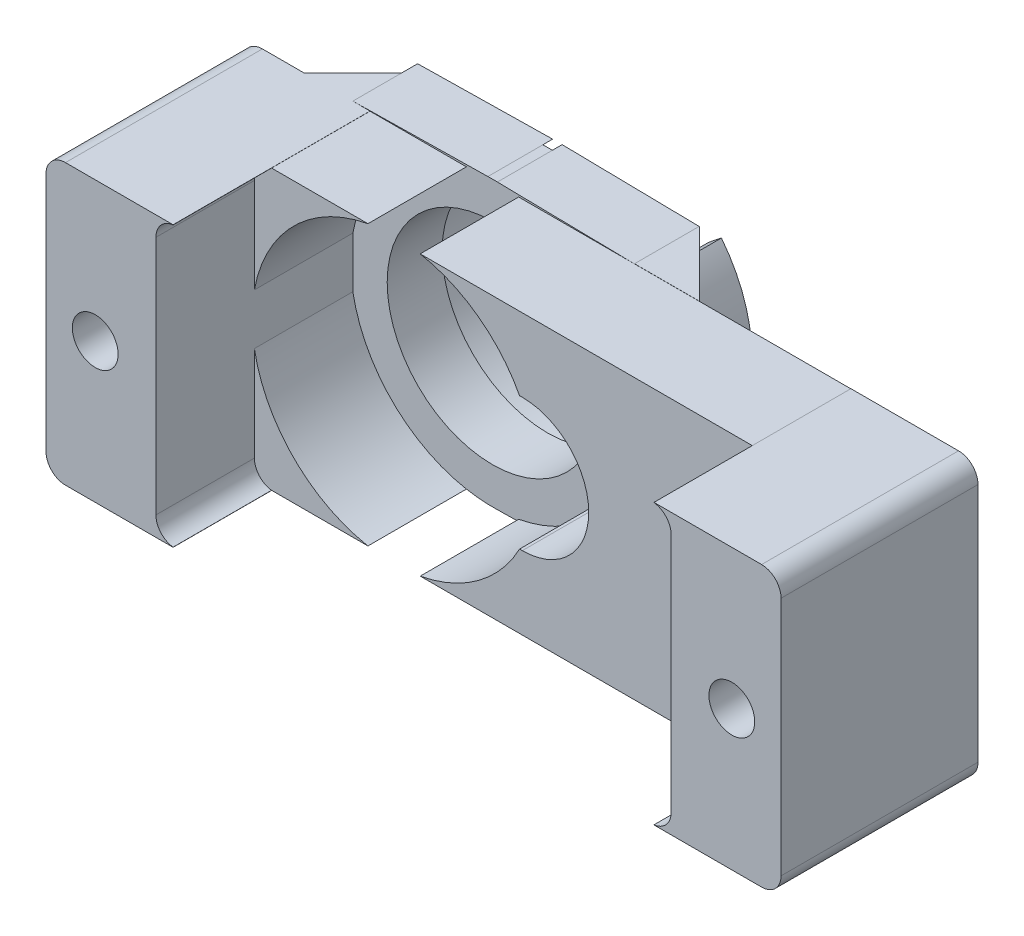
SolidWorks part; units mm, degrees
ref_plane "Front Plane" through (0, 0, 0) normal (0, 0, 1) x (1, 0, 0)
ref_plane "Top Plane" through (0, 0, 0) normal (0, 1, 0) x (1, 0, 0)
ref_plane "Right Plane" through (0, 0, 0) normal (1, 0, 0) x (0, 0, -1)
sketch "Sketch1" plane through (0, 0, 0) normal (0, 0, 1) x (1, 0, 0)
  line L1 (-16.05, -6.1) -> (16.05, -6.1)
  line L2 (-16.05, -6.1) -> (-16.05, 6.1)
  line L3 (-16.05, 6.1) -> (16.05, 6.1)
  line L4 (16.05, -6.1) -> (16.05, 6.1)
  line L5 (-16.05, -6.1) -> (16.05, 6.1) construction
  line L6 (-16.05, 6.1) -> (16.05, -6.1) construction
  point P0 (0, 0)
  dimension "D1" = 32.1
  dimension "D2" = 12.2
extrude "Boss-Extrude1" add sketch "Sketch1" along normal blind 4.3
fillet "Fillet1" radius 0.85 4 edges at (-16.05, -6.1, 2.15) (16.05, -6.1, 2.15) (16.05, 6.1, 2.15) (-16.05, 6.1, 2.15)
sketch "Sketch2" plane through (0, 0, 0) normal (0, 0, -1) x (-1, 0, 0)
  line L2 (-11.15, 5.25) -> (-11.15, -5.25)
  line L3 (-11.15, 5.25) -> (-11.15, -5.25) construction
  line L4 (-15.2, -6.1) -> (15.2, -6.1)
  line L5 (16.05, -5.25) -> (16.05, 5.25)
  line L6 (15.2, 6.1) -> (-15.2, 6.1)
  line L7 (-16.05, 5.25) -> (-16.05, -5.25)
  line L8 (-15.2, -6.1) -> (15.2, -6.1)
  line L9 (16.05, -5.25) -> (16.05, 5.25)
  line L10 (15.2, 6.1) -> (-15.2, 6.1)
  line L11 (-16.05, 5.25) -> (-16.05, -5.25)
  line L12 (-10.4, 6.1) -> (10.4, 6.1)
  line L13 (10.4, 6) -> (10.4, 6.1)
  line L14 (-10.4, 6) -> (-10.4, 6.1)
  line L15 (24.5614, 0) -> (-24.5614, 0) construction
  line L16 (0, -7.6317) -> (0, 7.6317) construction
  line L17 (11.15, 5.25) -> (11.15, -5.25)
  line L18 (-11.25, 5.25) -> (-11.25, -5.25)
  line L19 (-10.5, -6.0941) -> (-10.5, -6.2)
  line L20 (-10.5, -6.2) -> (10.5, -6.2)
  line L21 (10.5, -6.0941) -> (10.5, -6.2)
  line L22 (-10.4, -6) -> (-10.4, -6.1)
  line L23 (10.4, -6) -> (10.4, -6.1)
  line L24 (-10.4, -6.1) -> (10.4, -6.1)
  line L25 (11.25, 5.25) -> (11.25, -5.25)
  line L26 (10.5, 6.0941) -> (10.5, 6.2)
  line L27 (-10.5, 6.2) -> (10.5, 6.2)
  line L28 (-10.5, 6.0941) -> (-10.5, 6.2)
  arc A0 (-10.4, 6) -> (-11.15, 5.25) centre (-10.4, 5.25) ccw
  arc A1 (-10.4, 6) -> (-11.15, 5.25) centre (-10.4, 5.25) ccw construction
  arc A2 (10.4, 6) -> (11.15, 5.25) centre (10.4, 5.25) cw
  arc A3 (10.4, -6) -> (11.15, -5.25) centre (10.4, -5.25) ccw
  arc A12 (-10.4, -6) -> (-11.15, -5.25) centre (-10.4, -5.25) cw
  arc A13 (-10.5, 6.0941) -> (-11.25, 5.25) centre (-10.4, 5.25) ccw
  arc A14 (-10.5, -6.0941) -> (-11.25, -5.25) centre (-10.4, -5.25) cw
  arc A15 (10.5, -6.0941) -> (11.25, -5.25) centre (10.4, -5.25) ccw
  arc A16 (10.5, 6.0941) -> (11.25, 5.25) centre (10.4, 5.25) cw
  arc A17 (15.2, -6.1) -> (16.05, -5.25) centre (15.2, -5.25) ccw
  arc A19 (15.2, -6.1) -> (16.05, -5.25) centre (15.2, -5.25) ccw
  arc A21 (16.05, 5.25) -> (15.2, 6.1) centre (15.2, 5.25) ccw
  arc A23 (16.05, 5.25) -> (15.2, 6.1) centre (15.2, 5.25) ccw
  arc A25 (-15.2, 6.1) -> (-16.05, 5.25) centre (-15.2, 5.25) ccw
  arc A26 (-15.2, 6.1) -> (-16.05, 5.25) centre (-15.2, 5.25) ccw
  arc A27 (-16.05, -5.25) -> (-15.2, -6.1) centre (-15.2, -5.25) ccw
  arc A28 (-16.05, -5.25) -> (-15.2, -6.1) centre (-15.2, -5.25) ccw
  point P19 (0, -6.1)
  point P34 (0, 0)
  point P37 (0, 0)
  point P40 (0, 6.1)
  point P49 (11.15, 0)
  point P51 (-11.15, 0)
  line M13 (15.2, 6.1) -> (-15.2, 6.1)
  dimension "D1" = 0
  dimension "D2" = 0.1
extrude "Cut-Extrude1" cut sketch "Sketch2" against normal blind 10 contours A12 L22 L8 L23 A3 L17 A2 L13 L10 L14 A0 L2 | A14 L19 L8 L22 A12 L2 A0 L14 L28 A13 L18 M13 | A16 L26 L10 L13 A2 L17 A3 L23 L8 L21 A15 L25
sketch "Sketch3" plane through (0, 0, 4.3) normal (0, 0, 1) x (1, 0, 0)
  circle A0 centre (-13.9, 0) radius 1
  circle A1 centre (13.9, 0) radius 1
  dimension "D1" = 2
  dimension "D2" = 2
extrude "Cut-Extrude2" cut sketch "Sketch3" against normal blind 5 contours A1 | A0
sketch "Sketch5" plane through (0, 0, 0) normal (0, 0, -1) x (-1, 0, 0)
  line L0 (11.25, 5.25) -> (11.25, -5.25) construction
  line L1 (-11.25, 5.25) -> (-11.25, -5.25) construction
  line L2 (11.25, 5.25) -> (11.25, -5.25)
  line L3 (-11.25, 5.25) -> (-11.25, -5.25)
  line L4 (-0.45, 2.9) -> (-0.33, 2.9) construction
  line L5 (-0.33, -2.9) -> (-0.45, -2.9) construction
  line L6 (-0.45, 2.9) -> (-0.33, 2.9)
  line L7 (-0.33, -2.9) -> (-0.45, -2.9)
  line L8 (-10.5, 6.0941) -> (10.5, 6.0941)
  line L9 (-10.5, -6.0941) -> (10.5, -6.0941)
  line L10 (-10.5, -6.1) -> (-15.2, -6.1) construction
  line L11 (-16.05, -5.25) -> (-16.05, 5.25) construction
  line L12 (-15.2, 6.1) -> (-10.5, 6.1) construction
  line L13 (15.2, -6.1) -> (10.5, -6.1) construction
  line L14 (16.05, 5.25) -> (16.05, -5.25) construction
  line L15 (10.5, 6.1) -> (15.2, 6.1) construction
  line L16 (-10.5, -6.1) -> (-15.2, -6.1)
  line L17 (-16.05, -5.25) -> (-16.05, 5.25)
  line L18 (-15.2, 6.1) -> (-10.5, 6.1)
  line L19 (15.2, -6.1) -> (10.5, -6.1)
  line L20 (16.05, 5.25) -> (16.05, -5.25)
  line L21 (10.5, 6.1) -> (15.2, 6.1)
  line L22 (10.5, -6.1) -> (10.5, -6.0941)
  line L23 (10.5, 6.1) -> (10.5, 6.0941)
  arc A0 (11.25, 5.25) -> (10.5, 6.0941) centre (10.4, 5.25) ccw construction
  arc A1 (10.5, -6.0941) -> (11.25, -5.25) centre (10.4, -5.25) ccw construction
  arc A2 (-11.25, -5.25) -> (-10.5, -6.0941) centre (-10.4, -5.25) ccw construction
  arc A3 (-10.5, 6.0941) -> (-11.25, 5.25) centre (-10.4, 5.25) ccw construction
  arc A4 (11.25, 5.25) -> (10.5, 6.0941) centre (10.4, 5.25) ccw
  arc A5 (10.5, -6.0941) -> (11.25, -5.25) centre (10.4, -5.25) ccw
  arc A6 (-11.25, -5.25) -> (-10.5, -6.0941) centre (-10.4, -5.25) ccw
  arc A7 (-10.5, 6.0941) -> (-11.25, 5.25) centre (-10.4, 5.25) ccw
  arc A8 (6.712, -6) -> (11.15, -1.562) centre (5.15, 0) ccw construction
  arc A9 (11.15, 1.562) -> (6.712, 6) centre (5.15, 0) ccw construction
  arc A10 (3.588, 6) -> (-0.33, 2.9) centre (5.15, 0) ccw construction
  arc A11 (-0.33, -2.9) -> (3.588, -6) centre (5.15, 0) ccw construction
  arc A12 (-0.45, 2.9) -> (-0.45, -2.9) centre (-0.45, 0) ccw construction
  arc A13 (6.291, -6.0941) -> (11.25, -1.1091) centre (5.15, 0) ccw
  arc A14 (11.25, 1.1091) -> (6.291, 6.0941) centre (5.15, 0) ccw
  arc A15 (4.009, 6.0941) -> (-0.33, 2.9) centre (5.15, 0) ccw
  arc A16 (-0.33, -2.9) -> (4.009, -6.0941) centre (5.15, 0) ccw
  arc A17 (-0.45, 2.9) -> (-0.45, -2.9) centre (-0.45, 0) ccw
  arc A18 (-16.05, -5.25) -> (-15.2, -6.1) centre (-15.2, -5.25) ccw construction
  arc A19 (-15.2, 6.1) -> (-16.05, 5.25) centre (-15.2, 5.25) ccw construction
  arc A20 (15.2, -6.1) -> (16.05, -5.25) centre (15.2, -5.25) ccw construction
  arc A21 (16.05, 5.25) -> (15.2, 6.1) centre (15.2, 5.25) ccw construction
  arc A22 (-16.05, -5.25) -> (-15.2, -6.1) centre (-15.2, -5.25) ccw
  arc A23 (-15.2, 6.1) -> (-16.05, 5.25) centre (-15.2, 5.25) ccw
  arc A24 (15.2, -6.1) -> (16.05, -5.25) centre (15.2, -5.25) ccw
  arc A25 (16.05, 5.25) -> (15.2, 6.1) centre (15.2, 5.25) ccw
  circle A30 centre (-13.9, 0) radius 1
  dimension "D1" = 6.2
extrude "Boss-Extrude2" add sketch "Sketch5" along normal blind 4.3
sketch "Sketch6" plane through (0, 0, -4.3) normal (0, 0, -1) x (-1, 0, 0)
  line L0 (-0.33, -2.9) -> (-0.45, -2.9) construction
  line L1 (-0.45, 2.9) -> (-0.33, 2.9) construction
  line L2 (11.25, 1.1091) -> (11.25, -1.1091) construction
  line L3 (-0.33, -2.9) -> (-0.45, -2.9)
  line L4 (-0.45, 2.9) -> (-0.33, 2.9)
  line L5 (11.25, 1.1091) -> (11.25, -1.1091)
  arc A0 (4.009, 6.0941) -> (-0.33, 2.9) centre (5.15, 0) ccw construction
  arc A1 (-0.45, 2.9) -> (-0.45, -2.9) centre (-0.45, 0) ccw construction
  arc A2 (-0.33, -2.9) -> (4.009, -6.0941) centre (5.15, 0) ccw construction
  arc A3 (6.291, -6.0941) -> (11.25, -1.1091) centre (5.15, 0) ccw construction
  arc A4 (11.25, 1.1091) -> (6.291, 6.0941) centre (5.15, 0) ccw construction
  arc A5 (6.291, 6.0941) -> (-0.33, 2.9) centre (5.15, 0) ccw
  arc A6 (-0.45, 2.9) -> (-0.45, -2.9) centre (-0.45, 0) ccw
  arc A7 (-0.33, -2.9) -> (6.291, -6.0941) centre (5.15, 0) ccw
  arc A8 (6.291, -6.0941) -> (11.25, -1.1091) centre (5.15, 0) ccw
  arc A9 (11.25, 1.1091) -> (6.291, 6.0941) centre (5.15, 0) ccw
  circle A11 centre (5.15, 0) radius 4.6
  dimension "D1" = 9.2
extrude "Boss-Extrude3" add sketch "Sketch6" along normal blind 2.4 separate body
sketch "Sketch7" plane through (0, 0, -6.7) normal (0, 0, -1) x (-1, 0, 0)
  circle A0 centre (5.15, 0) radius 5.3536
  circle A1 centre (5.15, 0) radius 6.2
  arc A2 (-0.33, -2.9) -> (11.25, -1.1091) centre (5.15, 0) ccw construction
  circle A3 centre (5.15, 0) radius 5.5
  arc M3 (-0.33, -2.9) -> (11.25, -1.1091) centre (5.15, 0) ccw
  line M4 (11.25, -1.1091) -> (11.25, 1.1091)
  arc M5 (11.25, 1.1091) -> (-0.33, 2.9) centre (5.15, 0) ccw
  dimension "D1" = 11
sketch "Sketch11" plane through (0, 0, -6.7) normal (0, 0, -1) x (-1, 0, 0)
  line L0 (0, 3.4522) -> (-4.0855, 3.1867)
  line L1 (-4.0855, 3.1867) -> (-4.0855, -3.4029)
  line L2 (-4.0855, -3.4029) -> (0, -3.4522)
  circle A0 centre (5.15, 0) radius 6.2
  arc M1 (-0.33, -2.9) -> (11.25, -1.1091) centre (5.15, 0) ccw
  arc M3 (11.25, 1.1091) -> (-0.33, 2.9) centre (5.15, 0) ccw
  line M4 (-0.33, 2.9) -> (-0.45, 2.9)
  arc M5 (-0.45, 2.9) -> (-0.45, -2.9) centre (-0.45, 0) ccw
  line M6 (-0.45, -2.9) -> (-0.33, -2.9)
extrude "Cut-Extrude4" cut sketch "Sketch11" against normal up to vertex (2.4 mm away) contours A0 M4 M5 M6 | L1 L2 L0 M1 M6 M5 M4 M3
extrude "Boss-Extrude4" add sketch "Sketch7" along normal up to vertex contours A1 A3 M5 M3 M4
sketch "Sketch8" plane through (0, 0, -9.4294) normal (0, 0, -1) x (-1, 0, 0)
  line L0 (9.4671, 3.4077) -> (10.0166, 3.8414)
  line L1 (0.8329, 3.4077) -> (0.2834, 3.8414)
  line L2 (9.4671, 3.4077) -> (0.8329, 3.4077)
  line L3 (10.0166, 3.8414) -> (10.0166, 6.3111)
  line L4 (10.0166, 6.3111) -> (0.2834, 6.3111)
  line L5 (0.2834, 6.3111) -> (0.2834, 3.8414)
  circle A0 centre (5.15, 0) radius 5.5 construction
  arc A1 (11.25, 1.1091) -> (11.25, -1.1091) centre (5.15, 0) ccw construction
extrude "Cut-Extrude3" cut sketch "Sketch8" against normal up to surface (2.7294 mm away) up to face at (-9.75, 0, -6.7)
sketch "Sketch12" plane through (0, -6.0941, 0) normal (0, -1, 0) x (1, 0, 0)
  line L0 (1.05, -7.1284) -> (3.8784, -4.3)
  line L1 (1.05, -9.4294) -> (1.05, -4.3) construction
  line L2 (10.5, -4.3) -> (-4.009, -4.3) construction
  line L3 (-11.25, -6.4213) -> (-13.3713, -4.3)
  line L4 (-11.25, -9.4294) -> (-11.25, -4.3) construction
  line L5 (-15.2, -4.3) -> (-10.5, -4.3) construction
  line L6 (-11.25, -6.4213) -> (-11.25, -4.3)
  line L7 (-11.25, -4.3) -> (-13.3713, -4.3)
  line L8 (3.8784, -4.3) -> (1.05, -4.3)
  line L9 (10.5, -4.3) -> (-4.009, -4.3) construction
  line L10 (1.05, -4.3) -> (-11.25, -4.3) construction
  line L11 (1.05, -4.3) -> (1.05, -7.1284)
  dimension "D1" = 45
  dimension "D2" = 45
  dimension "D3" = 4
  dimension "D4" = 3
extrude "Boss-Extrude5" add sketch "Sketch12" against normal up to vertex (12.1941 mm away)
sketch "Sketch13" plane through (0, 0, -4.3) normal (0, 0, -1) x (-1, 0, 0)
  line L0 (-1.05, 6.0941) -> (5.15, 6.2)
  line L1 (5.15, 6.2) -> (11.25, 6.1)
  line L2 (10.5, 6.1) -> (11.25, 6.1) construction
  line L3 (11.25, 6.1) -> (11.25, 1.1091) construction
  line L4 (11.25, 6.1) -> (11.25, -6.0941)
  line L5 (11.25, -6.0941) -> (5.15, -6.2)
  line L6 (5.15, -6.2) -> (-1.05, -6.0941)
  line L7 (-1.05, -6.0941) -> (-1.05, 6.0941)
  circle A0 centre (5.15, 0) radius 6.2
  line M6 (11.25, -6.0941) -> (11.25, -1.1091)
  arc M7 (11.25, -1.1091) -> (6.291, -6.0941) centre (5.15, 0) cw
  line M8 (6.291, -6.0941) -> (10.5, -6.0941)
  line M9 (10.5, -6.0941) -> (10.5, -6.1)
  line M10 (10.5, -6.1) -> (15.2, -6.1)
extrude "Boss-Extrude6" add sketch "Sketch13" along normal up to vertex contours A0 L0 L7 | A0 L4 L1 | L5 M6 M7 M8 M9 M10 | A0 L7 L6
sketch "Sketch18" plane through (0, 0, -7.1284) normal (0, 0, -1) x (-1, 0, 0)
  line L0 (11.25, 6.1) -> (11.25, 1.1091) construction
  line L1 (-1.05, 0) -> (-1.05, 6.0941) construction
  line L2 (11.25, 6.1) -> (11.25, 1.1091)
  line L3 (-1.05, 0) -> (-1.05, 6.0941)
  line L4 (-1.05, 6.0941) -> (-1.05, 9.5172)
  line L5 (-1.05, 9.5172) -> (11.25, 9.5172)
  line L6 (11.25, 9.5172) -> (11.25, 6.1)
  line L7 (1.7219, 5.166) -> (8.5781, 5.166)
  arc A0 (11.25, 1.1091) -> (10.0166, 3.8414) centre (5.15, 0) ccw construction
  arc A1 (10.0166, 3.8414) -> (5.3532, 6.1967) centre (5.15, 0) ccw construction
  arc A2 (0.2834, 3.8414) -> (-1.05, 0) centre (5.15, 0) ccw construction
  arc A3 (4.9383, 6.1964) -> (0.2834, 3.8414) centre (5.15, 0) ccw construction
  arc A4 (11.25, 1.1091) -> (10.0166, 3.8414) centre (5.15, 0) ccw
  arc A5 (10.0166, 3.8414) -> (8.5781, 5.166) centre (5.15, 0) ccw
  arc A6 (0.2834, 3.8414) -> (-1.05, 0) centre (5.15, 0) ccw
  arc A7 (1.7219, 5.166) -> (0.2834, 3.8414) centre (5.15, 0) ccw
extrude "Cut-Extrude10" [suppressed] cut sketch "Sketch18" against normal up to surface (0.4284 mm away)
